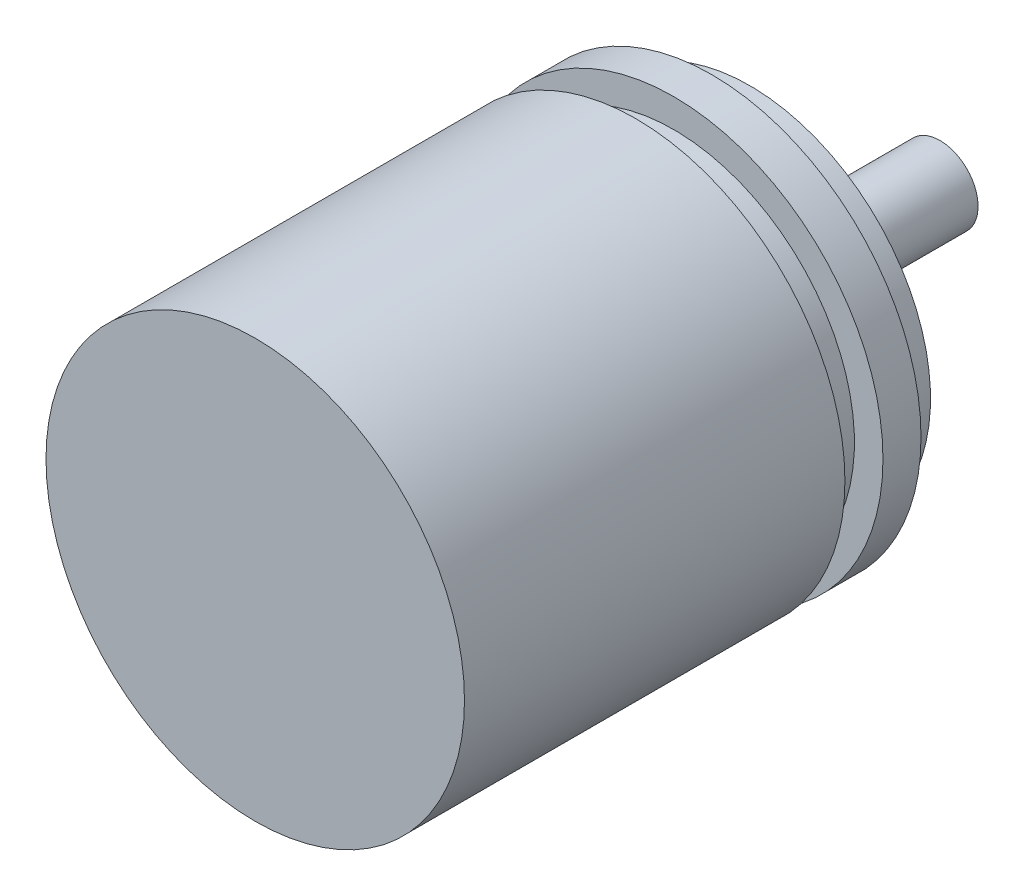
SolidWorks part; units mm, degrees
ref_plane "Front" through (0, 0, 0) normal (0, 0, 1) x (1, 0, 0)
ref_plane "Top" through (0, 0, 0) normal (0, 1, 0) x (1, 0, 0)
ref_plane "Right" through (0, 0, 0) normal (1, 0, 0) x (0, 0, -1)
sketch "Sketch1" plane through (0, 0, 0) normal (0, 0, 1) x (1, 0, 0)
  circle A0 centre (0, 0) radius 2
  dimension "D1" = 4
extrude "Boss-Extrude1" add sketch "Sketch1" along normal blind 10
sketch "Sketch2" plane through (0, 0, 10) normal (0, 0, 1) x (1, 0, 0)
  circle A0 centre (0, 0) radius 9.5
  dimension "D1" = 19
extrude "Boss-Extrude2" add sketch "Sketch2" along normal blind 2
sketch "Sketch3" plane through (0, 0, 12) normal (0, 0, 1) x (1, 0, 0)
  circle A0 centre (0, 0) radius 11
  dimension "D1" = 22
extrude "Boss-Extrude3" add sketch "Sketch3" along normal blind 2
sketch "Sketch4" plane through (0, 0, 14) normal (0, 0, 1) x (1, 0, 0)
  circle A0 centre (0, 0) radius 9.5
  circle A1 centre (0, 0) radius 9.5 construction
extrude "Boss-Extrude4" add sketch "Sketch4" along normal blind 2
sketch "Sketch5" plane through (0, 0, 16) normal (0, 0, 1) x (1, 0, 0)
  circle A0 centre (0, 0) radius 11
  circle A1 centre (0, 0) radius 11 construction
extrude "Boss-Extrude5" add sketch "Sketch5" along normal blind 20
sketch "Sketch6" plane through (0, 0, 10) normal (0, 0, -1) x (-1, 0, 0)
  circle A0 centre (0, 0) radius 7.5 construction
  circle A1 centre (-7.5, 0) radius 1.25
  circle A2 centre (7.5, 0) radius 1.25
  dimension "D1" = 15
  dimension "D2" = 2.5
extrude "Cut-Extrude1" cut sketch "Sketch6" against normal blind 5
